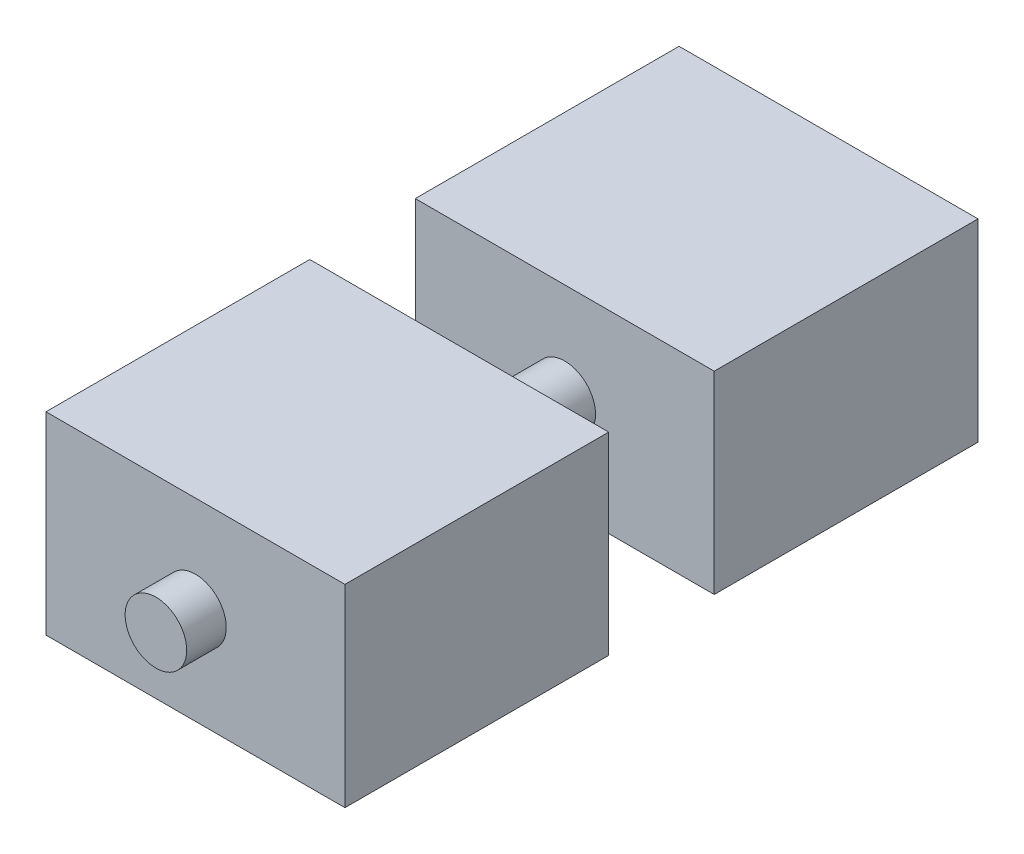
SolidWorks part; units mm, degrees
ref_plane "前视基准面" through (0, 0, 0) normal (0, 0, 1) x (1, 0, 0)
ref_plane "上视基准面" through (0, 0, 0) normal (0, 1, 0) x (1, 0, 0)
ref_plane "右视基准面" through (0, 0, 0) normal (1, 0, 0) x (0, 0, -1)
sketch "草图1" plane through (0, 0, 0) normal (0, 1, 0) x (1, 0, 0)
  line L0 (0, 15) -> (0, 42) construction
  line L1 (-17, 15) -> (17, 15)
  line L2 (-17, 15) -> (-17, -15)
  line L3 (-17, -15) -> (17, -15)
  line L4 (17, 15) -> (17, -15)
  line L5 (-17, 15) -> (17, -15) construction
  line L6 (-17, -15) -> (17, 15) construction
  line L8 (-17, 57) -> (17, 57)
  line L9 (-17, 57) -> (-17, 27)
  line L10 (-17, 27) -> (17, 27)
  line L11 (17, 57) -> (17, 27)
  line L12 (-17, 57) -> (17, 27) construction
  line L13 (-17, 27) -> (17, 57) construction
  point P0 (0, 0)
  dimension "D1" = 30
  dimension "D2" = 34
  dimension "D3" = 27
  dimension "D4" = 30
  dimension "D5" = 34
extrude "凸台-拉伸1" add sketch "草图1" along normal blind 22
ref_plane "基准面1" through (0, 0, 15) normal (0, 0, 1) x (1, 0, 0)
sketch "草图2" plane through (0, 0, 15) normal (0, 0, 1) x (1, 0, 0)
  line L0 (-17, 22) -> (17, 0) construction
  circle A0 centre (0, 11) radius 3.5
  dimension "D1" = 7
extrude "凸台-拉伸2" add sketch "草图2" along normal blind 4.5 and the other way blind 75
ref_plane "基准面2" through (0, 0, 0) normal (0, -1, 0) x (-1, 0, 0)
sketch "草图3" plane through (0, 0, 0) normal (0, -1, 0) x (-1, 0, 0)
  line L0 (-17, 57) -> (17, 27) construction
  line L1 (-17, 15) -> (17, -15) construction
  line L2 (-11.75, 33.25) -> (11.75, 33.25) construction
  line L3 (-11.75, 33.25) -> (-11.75, 50.75) construction
  line L4 (-11.75, 50.75) -> (11.75, 50.75) construction
  line L5 (11.75, 33.25) -> (11.75, 50.75) construction
  line L6 (-11.75, 33.25) -> (11.75, 50.75) construction
  line L7 (-11.75, 50.75) -> (11.75, 33.25) construction
  line L9 (-12, -9) -> (12, -9) construction
  line L10 (-12, -9) -> (-12, 9) construction
  line L11 (-12, 9) -> (12, 9) construction
  line L12 (12, -9) -> (12, 9) construction
  line L13 (-12, -9) -> (12, 9) construction
  line L14 (-12, 9) -> (12, -9) construction
  circle A0 centre (-11.75, 33.25) radius 2.05
  circle A1 centre (11.75, 33.25) radius 2.05
  circle A2 centre (11.75, 50.75) radius 2.05
  circle A3 centre (-11.75, 50.75) radius 2.05
  circle A4 centre (-12, -9) radius 2.05
  circle A5 centre (-12, 9) radius 2.05
  circle A6 centre (12, 9) radius 2.05
  circle A7 centre (12, -9) radius 2.05
  point P4 (0, 42)
  point P17 (0, 0)
  dimension "D3" = 4.1
  dimension "D4" = 4.1
  dimension "D5" = 4.1
  dimension "D6" = 4.1
  dimension "D9" = 4.1
  dimension "D10" = 4.1
  dimension "D11" = 4.1
  dimension "D12" = 4.1
  dimension "D1" = 23.5
  dimension "D2" = 17.5
  dimension "D7" = 24
  dimension "D8" = 18
extrude "切除-拉伸1" cut sketch "草图3" against normal blind 5
